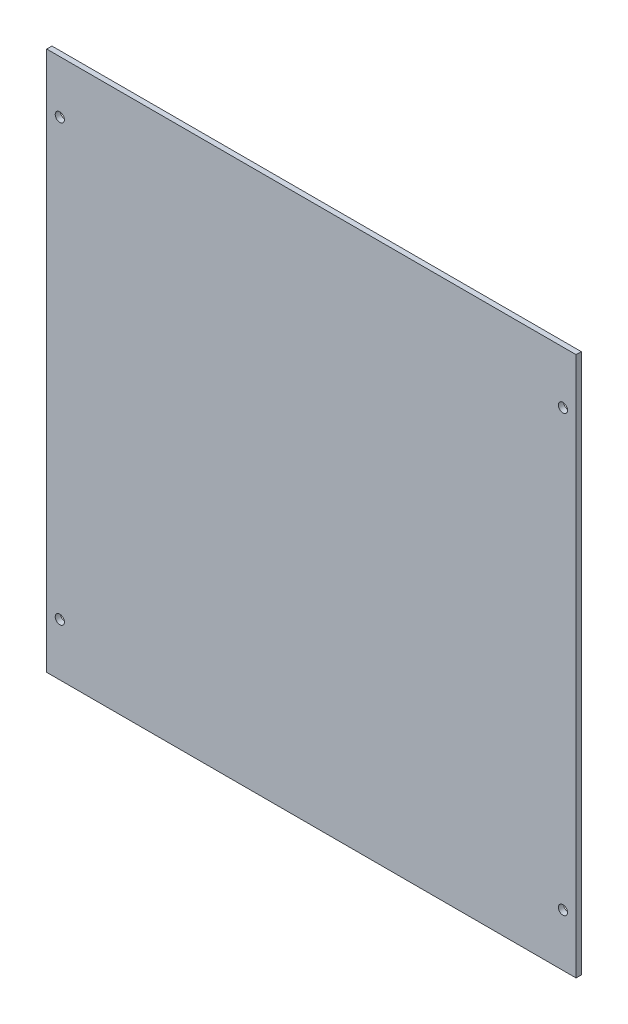
SolidWorks part; units mm, degrees
ref_plane "Front Plane" through (0, 0, 0) normal (0, 0, 1) x (1, 0, 0)
ref_plane "Top Plane" through (0, 0, 0) normal (0, 1, 0) x (1, 0, 0)
ref_plane "Right Plane" through (0, 0, 0) normal (1, 0, 0) x (0, 0, -1)
sketch "Sketch1" plane through (0, 0, 0) normal (0, 0, 1) x (1, 0, 0)
  line L1 (0, 0) -> (202, 0)
  line L2 (0, 0) -> (0, 206)
  line L3 (0, 206) -> (202, 206)
  line L4 (202, 0) -> (202, 206)
  circle A0 centre (5, 186) radius 1.75
  circle A1 centre (197, 186) radius 1.75
  circle A2 centre (5, 20) radius 1.75
  circle A3 centre (197, 20) radius 1.75
  dimension "D4" = 5
  dimension "D5" = 5
  dimension "D6" = 5
  dimension "D7" = 20
  dimension "D8" = 20
  dimension "D9" = 20
  dimension "D10" = 20
  dimension "D11" = 3.5
  dimension "D1" = 206
  dimension "D2" = 202
  dimension "D3" = 5
extrude "Boss-Extrude1" add sketch "Sketch1" along normal blind 2
